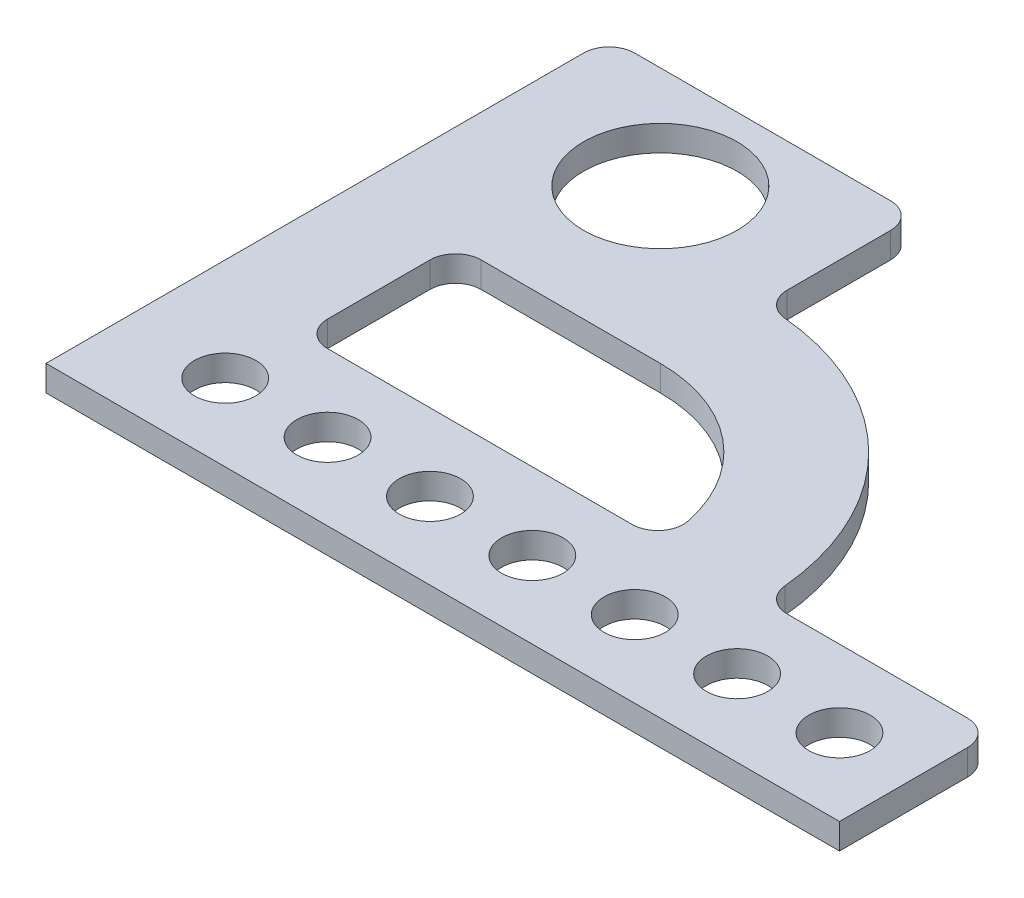
SolidWorks part; units mm, degrees
ref_plane "Front Plane" through (0, 0, 0) normal (0, 0, 1) x (1, 0, 0)
ref_plane "Top Plane" through (0, 0, 0) normal (0, 1, 0) x (1, 0, 0)
ref_plane "Right Plane" through (0, 0, 0) normal (1, 0, 0) x (0, 0, -1)
sketch "Sketch1" plane through (0, 0, 0) normal (0, 1, 0) x (1, 0, 0)
  line L0 (114.7723, 30) -> (150, 30)
  line L1 (25, 30) -> (84.4949, 30)
  line L3 (0, 0) -> (155, 0)
  line L4 (155, 25) -> (155, 0)
  line L5 (25, 30) -> (60, 30)
  line L7 (5, 110) -> (55, 110)
  line L8 (60, 84.7723) -> (60, 105)
  line L9 (25, 60) -> (60, 60)
  line L10 (20, 55) -> (20, 35)
  line L11 (25, 30) -> (84.4949, 30)
  line L13 (0, 105) -> (0, 0)
  arc A0 (64.5455, 79.793) -> (109.793, 34.5455) centre (60, 30) cw
  circle A1 centre (30, 90) radius 15
  arc A2 (89.3939, 36) -> (60, 60) centre (60, 30) ccw
  arc A3 (55, 110) -> (60, 105) centre (55, 105) cw
  arc A4 (0, 105) -> (5, 110) centre (5, 105) cw
  arc A5 (84.4949, 30) -> (89.3939, 36) centre (84.4949, 35) ccw
  arc A6 (25, 30) -> (20, 35) centre (25, 35) cw
  arc A7 (20, 55) -> (25, 60) centre (25, 55) cw
  arc A8 (155, 25) -> (150, 30) centre (150, 25) ccw
  circle A9 centre (20, 15) radius 6
  circle A10 centre (40, 15) radius 6
  circle A11 centre (60, 15) radius 6
  circle A12 centre (80, 15) radius 6
  circle A13 centre (100, 15) radius 6
  circle A14 centre (120, 15) radius 6
  circle A15 centre (140, 15) radius 6
  arc A16 (64.5455, 79.793) -> (60, 84.7723) centre (65, 84.7723) cw
  arc A17 (114.7723, 30) -> (109.793, 34.5455) centre (114.7723, 35) cw
  point P17 (60, 110)
  point P20 (0, 110)
  point P29 (20, 60)
  point P30 (155, 30)
  point P47 (60, 80)
  point P50 (110, 30)
  dimension "D7" = 30
  dimension "D9" = 50
  dimension "D13" = 5
  dimension "D14" = 5
  dimension "D15" = 5
  dimension "D3" = 5
  dimension "D11" = 12
  dimension "D20" = 5
  dimension "D21" = 5
  dimension "D1" = 155
  dimension "D2" = 30
  dimension "D4" = 110
  dimension "D5" = 60
  dimension "D6" = 30
  dimension "D8" = 20
  dimension "D10" = 30
  dimension "D12" = 20
  dimension "D16" = 15
  dimension "D19" = 120
  dimension "D22" = 30
  dimension "D23" = 20
  dimension "D18" = 7
extrude "Boss-Extrude1" add sketch "Sketch1" along normal blind 5 contours L0 A17 A0 A16 L8 A3 L7 A4 L13 L3 L4 A8 L10 A7 L9 A2 A5 L1 A6 A1 A9 A10 A11 A12 A13 A14 A15
equation "\"a\"=60"
equation "\"D5@Sketch1\"=\"a\""
equation "\"a/2\"=30"
equation "\"D6@Sketch1\"=\"a\"/2"
